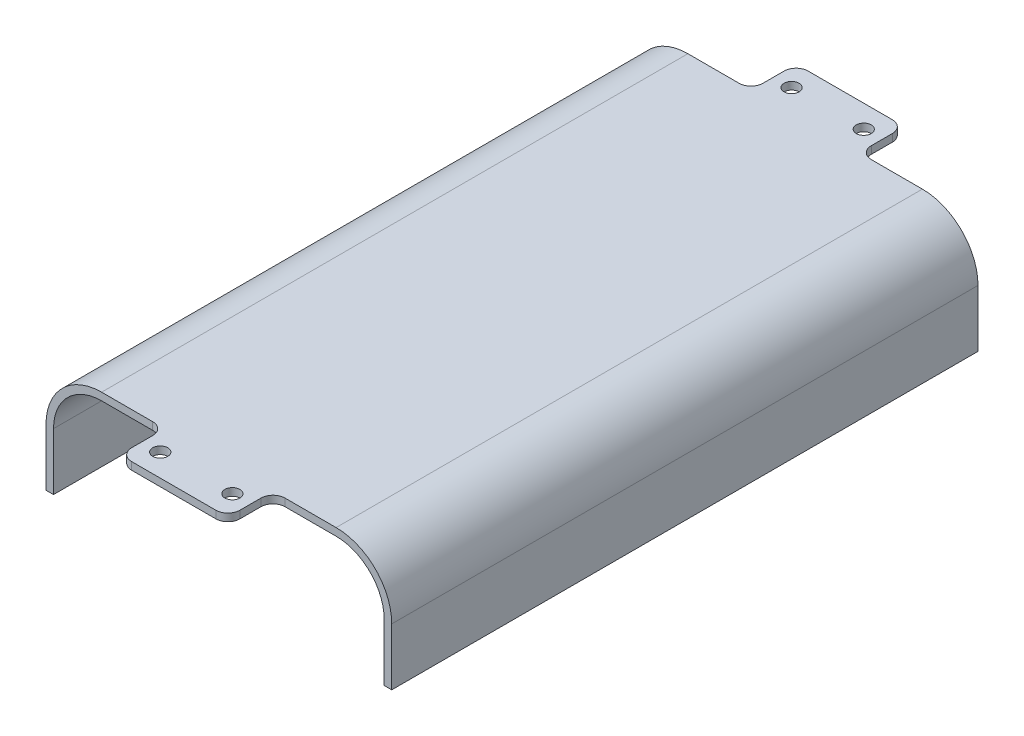
SolidWorks part; units mm, degrees
ref_plane "前视基准面" through (0, 0, 0) normal (0, 0, 1) x (1, 0, 0)
ref_plane "上视基准面" through (0, 0, 0) normal (0, 1, 0) x (1, 0, 0)
ref_plane "右视基准面" through (0, 0, 0) normal (1, 0, 0) x (0, 0, -1)
other "Configuration Table"
sketch "草图1" plane through (0, 0, 0) normal (0, 0, 1) x (1, 0, 0)
  line L1 (-39, 17.5) -> (39, 17.5)
  line L2 (-55, 1.5) -> (-55, -17.5)
  line L3 (-55, -17.5) -> (55, -17.5)
  line L4 (55, 1.5) -> (55, -17.5)
  arc A1 (-39, 17.5) -> (-55, 1.5) centre (-39, 1.5) ccw
  arc A2 (39, 17.5) -> (55, 1.5) centre (39, 1.5) cw
  point P0 (0, 0)
extrude "凸台-拉伸1" add sketch "草图1" along normal blind 225
shell "抽壳2" thickness 2.5
sketch "草图2" plane through (0, 20, 0) normal (0, 1, 0) x (1, 0, 0)
  line L1 (-14, 0) -> (-74.0332, 0)
  line L6 (-74.0332, 0) -> (-74.0332, -15)
  line L7 (-74.0332, -15) -> (-57.5, -15)
  line L9 (-18, -4) -> (-18, -11)
  line L10 (-22, -15) -> (-57.5, -15)
  line L11 (-57.5, -225) -> (-57.5, 0) construction
  line L15 (57.5, -15) -> (57.5, 0)
  line L16 (22, -15) -> (57.5, -15)
  line L17 (18, -4) -> (18, -11)
  line L18 (14, 0) -> (57.5, 0)
  line L19 (18, -221) -> (18, -214)
  line L20 (22, -210) -> (57.5, -210)
  line L21 (57.5, -210) -> (57.5, -225)
  line L22 (14, -225) -> (57.5, -225)
  line L23 (-18, -221) -> (-18, -214)
  line L24 (-22, -210) -> (-57.5, -210)
  line L25 (-74.0332, -210) -> (-57.5, -210)
  line L26 (-74.0332, -225) -> (-74.0332, -210)
  line L27 (-14, -225) -> (-74.0332, -225)
  circle A0 centre (-12, -7.5) radius 2.5
  circle A1 centre (12, -7.5) radius 2.5
  arc A2 (-18, -11) -> (-22, -15) centre (-22, -11) cw
  arc A3 (-18, -4) -> (-14, 0) centre (-14, -4) cw
  arc A4 (18, -4) -> (14, 0) centre (14, -4) ccw
  arc A5 (22, -15) -> (18, -11) centre (22, -11) cw
  circle A6 centre (-12, -217.5) radius 2.5
  circle A7 centre (12, -217.5) radius 2.5
  arc A8 (18, -221) -> (14, -225) centre (14, -221) cw
  arc A9 (22, -210) -> (18, -214) centre (22, -214) ccw
  arc A10 (-18, -221) -> (-14, -225) centre (-14, -221) ccw
  arc A11 (-18, -214) -> (-22, -210) centre (-22, -214) ccw
  point P28 (-18, -15)
  point P37 (18, -15)
  dimension "D1" = 4
  dimension "D2" = 4
  dimension "D3" = 4
  dimension "D4" = 4
extrude "切除-拉伸1" cut sketch "草图2" against normal through all
